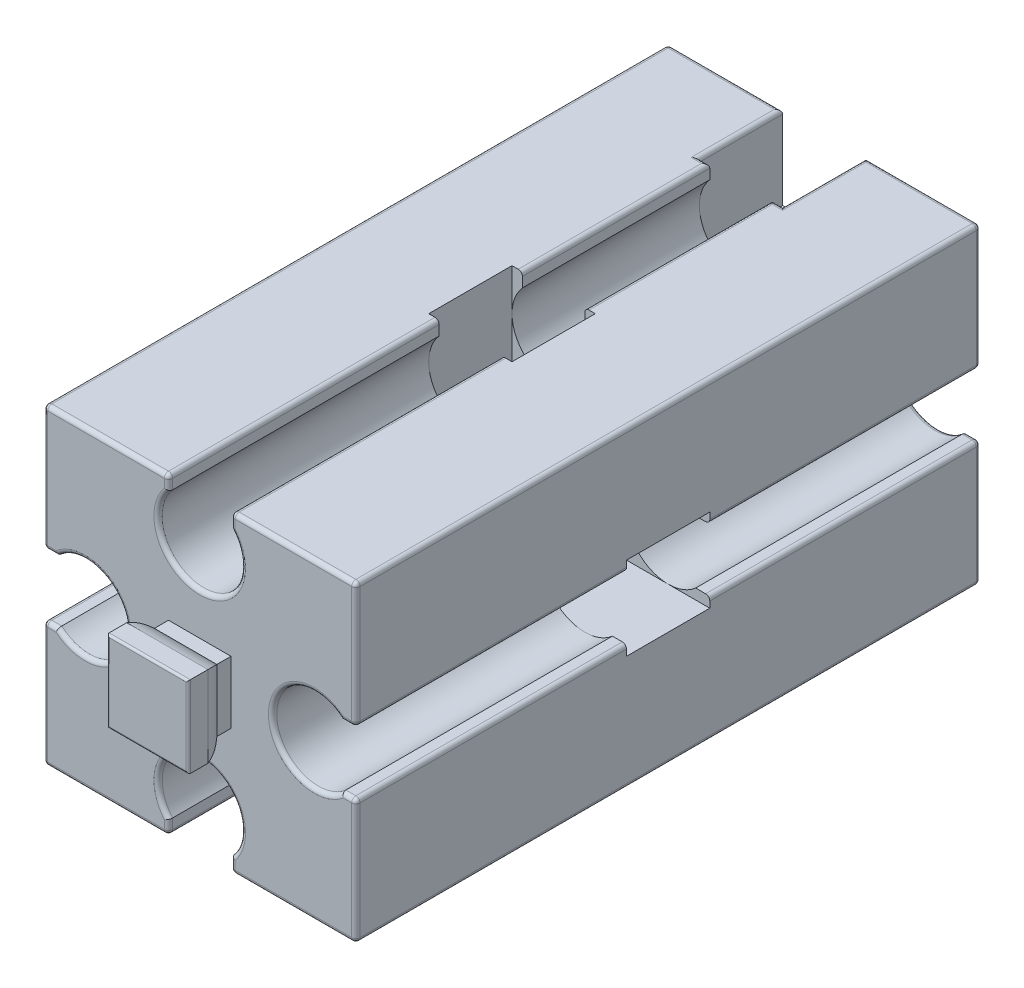
SolidWorks part; units mm, degrees
ref_plane "前视基准面" through (0, 0, 0) normal (0, 0, 1) x (1, 0, 0)
ref_plane "上视基准面" through (0, 0, 0) normal (0, 1, 0) x (1, 0, 0)
ref_plane "右视基准面" through (0, 0, 0) normal (1, 0, 0) x (0, 0, -1)
sketch "草图1" plane through (0, 0, 0) normal (0, 0, 1) x (1, 0, 0)
  line L1 (-7.5, -7.5) -> (7.5, -7.5)
  line L2 (-7.5, -7.5) -> (-7.5, 7.5)
  line L3 (-7.5, 7.5) -> (7.5, 7.5)
  line L4 (7.5, -7.5) -> (7.5, 7.5)
extrude "凸台-拉伸1" add sketch "草图1" against normal blind 30
sketch "草图2" plane through (0, 0, 0) normal (0, 1, 0) x (1, 0, 0)
  line L0 (-7.5, 0) -> (7.5, 0) construction
  line L1 (-1.5, 0) -> (1.5, 0)
  line L2 (-1.5, 0) -> (-1.5, -1)
  line L3 (-1.5, -1) -> (1.5, -1)
  line L4 (1.5, 0) -> (1.5, -1)
extrude "凸台-拉伸2" add sketch "草图2" along normal blind 1.5 and the other way blind 1.5
sketch "草图3" plane through (0, 0, 0) normal (0, 1, 0) x (1, 0, 0)
  line L1 (-1.95, -2.5) -> (1.95, -2.5)
  line L2 (-1.95, -2.5) -> (-1.95, -1.5556)
  line L3 (1.95, -2.5) -> (1.95, -1.5556)
  line L4 (-1.5, 0) -> (-1.5, -1) construction
  line L5 (-1.5, -0.6771) -> (1.5, -0.6771)
  arc A0 (-1.5, -0.6771) -> (-1.95, -1.5556) centre (0, -2) ccw
  arc A1 (1.95, -1.5556) -> (1.5, -0.6771) centre (0, -2) ccw
extrude "凸台-拉伸3" add sketch "草图3" along normal blind 3 and the other way blind 3
sketch "草图5" plane through (0, 0, 0) normal (0, 0, 1) x (1, 0, 0)
  line L0 (-7.5, -7.5) -> (7.5, -7.5) construction
  line L1 (-1.5, -7.5) -> (1.5, -7.5)
  line L2 (-1.5, -7.5) -> (-1.5, -6.8229)
  line L3 (-7.5, 7.5) -> (-7.5, -7.5) construction
  line L4 (1.5, -7.5) -> (1.5, -6.8229)
  line L6 (1.5, 7.5) -> (1.5, 6.8229)
  line L7 (-1.5, 7.5) -> (-1.5, 6.8229)
  line L8 (-1.5, 7.5) -> (1.5, 7.5)
  line L9 (-7.5, 1.5) -> (-6.8229, 1.5)
  line L10 (-7.5, 1.5) -> (-7.5, -1.5)
  line L11 (-7.5, -1.5) -> (-6.8229, -1.5)
  line L12 (7.5, -1.5) -> (6.8229, -1.5)
  line L13 (7.5, 1.5) -> (7.5, -1.5)
  line L14 (7.5, 1.5) -> (6.8229, 1.5)
  arc A0 (1.5, -6.8229) -> (-1.5, -6.8229) centre (0, -5.5) ccw
  arc A1 (1.5, 6.8229) -> (-1.5, 6.8229) centre (0, 5.5) cw
  arc A2 (-6.8229, -1.5) -> (-6.8229, 1.5) centre (-5.5, 0) ccw
  arc A3 (6.8229, -1.5) -> (6.8229, 1.5) centre (5.5, 0) cw
extrude "切除-拉伸2" cut sketch "草图5" against normal through all
sketch "草图6" plane through (0, 7.5, 0) normal (0, 1, 0) x (-1, 0, 0)
  line L0 (1.5, -30) -> (7.5, -30) construction
  line L1 (2, -30) -> (-2, -30)
  line L2 (2, -30) -> (2, -26)
  line L3 (2, -26) -> (-2, -26)
  line L4 (-2, -30) -> (-2, -26)
extrude "切除-拉伸3" cut sketch "草图6" against normal blind 4
sketch "草图9" plane through (0, -7.5, 0) normal (0, -1, 0) x (1, 0, 0)
  line L0 (-7.5, -30) -> (-1.5, -30) construction
  line L1 (-2, -30) -> (2, -30)
  line L2 (-2, -30) -> (-2, -26)
  line L3 (-2, -26) -> (2, -26)
  line L4 (2, -30) -> (2, -26)
extrude "切除-拉伸5" cut sketch "草图9" against normal blind 4
sketch "草图11" plane through (0, 0, 0) normal (0, 1, 0) x (1, 0, 0)
  line L0 (2, 30) -> (-2, 30) construction
  line L1 (-1.5, 30) -> (1.5, 30)
  line L2 (-1.5, 30) -> (-1.5, 29.3229)
  line L4 (1.5, 30) -> (1.5, 29.3229)
  arc A0 (-1.5, 29.3229) -> (1.5, 29.3229) centre (0, 28) ccw
extrude "切除-拉伸6" cut sketch "草图11" against normal through all and the other way through all
sketch "草图12" plane through (0, 0, 0) normal (1, 0, 0) x (0, 0, -1)
  line L0 (-2.5, 3) -> (-2.5, 1.95)
  line L1 (-2.5, 1.95) -> (-1.5556, 1.95)
  line L2 (-2.5, -1.95) -> (-1.5556, -1.95)
  line L5 (-2.5, -1.95) -> (-2.5, -3)
  line L6 (-2.5, 3) -> (-0.6771, 3)
  line L7 (-0.6771, 3) -> (-0.6771, 1.5)
  line L8 (-2.5, -3) -> (-0.6771, -3)
  line L9 (-0.6771, -3) -> (-0.6771, -1.5)
  arc A0 (-0.6771, 1.5) -> (-1.5556, 1.95) centre (-2, 0) ccw
  arc A1 (-1.5556, -1.95) -> (-0.6771, -1.5) centre (-2, 0) ccw
extrude "切除-拉伸7" cut sketch "草图12" against normal up to next and the other way up to next
fillet "圆角2" radius 0.1 4 edges at (-1.95, 0, 2.5) (0, -1.95, 2.5) (1.95, 0, 2.5) (0, 1.95, 2.5)
fillet "圆角3" radius 0.2 54 edges at (-4.75, 7.5, -30) (-7.5, 4.5, -30) (-7.1614, 1.5, -30) (-3.5, 0, -30) (-7.1614, -1.5, -30) (-7.5, -4.5, -30) (-4.75, -7.5, -30) (4.75, -7.5, -30) (7.5, -4.5, -30) (7.1614, -1.5, -30) (3.5, 0, -30) (7.1614, 1.5, -30) (7.5, 4.5, -30) (4.75, 7.5, -30) (7.1614, -1.5, 0) (7.5, -4.5, 0) (4.5, -7.5, 0) (1.5, -7.1614, 0) (0, -3.5, 0) (-1.5, -7.1614, 0) (-4.5, -7.5, 0) (-7.5, -4.5, 0) (-7.1614, -1.5, 0) (-3.5, 0, 0) (-7.1614, 1.5, 0) (-7.5, 4.5, 0) (-4.5, 7.5, 0) (-1.5, 7.1614, 0) (0, 3.5, 0) (1.5, 7.1614, 0) (4.5, 7.5, 0) (7.5, 4.5, 0) (7.1614, 1.5, 0) (3.5, 0, 0) (-7.5, -7.5, -15) (-1.5, -7.5, -13) (-1.75, -7.5, -26) (-2, -7.5, -28) (1.5, -7.5, -13) (7.5, -7.5, -15) (2, -7.5, -28) (1.75, -7.5, -26) (7.5, 7.5, -15) (1.5, 7.5, -13) (1.75, 7.5, -26) (2, 7.5, -28) (-1.75, 7.5, -26) (-1.5, 7.5, -13) (-7.5, 7.5, -15) (-2, 7.5, -28) (-7.5, 1.5, -15) (-7.5, -1.5, -15) (7.5, -1.5, -15) (7.5, 1.5, -15)
sketch "草图13" plane through (7.5, 0, 0) normal (1, 0, 0) x (0, 0, -1)
  circle A0 centre (15, 0) radius 2
extrude "切除-拉伸8" cut sketch "草图13" against normal through all
sketch "草图14" plane through (7.5, 0, 0) normal (1, 0, 0) x (0, 0, -1)
  line L1 (13, -2) -> (17, -2)
  line L2 (13, -2) -> (13, 2)
  line L3 (13, 2) -> (17, 2)
  line L4 (17, -2) -> (17, 2)
extrude "切除-拉伸9" cut sketch "草图14" against normal blind 4
sketch "草图15" plane through (-7.5, 0, 0) normal (-1, 0, 0) x (0, 0, 1)
  line L1 (-17, -2) -> (-13, -2)
  line L2 (-17, -2) -> (-17, 2)
  line L3 (-17, 2) -> (-13, 2)
  line L4 (-13, -2) -> (-13, 2)
extrude "切除-拉伸10" cut sketch "草图15" against normal blind 4
sketch "草图16" plane through (0, 7.5, 0) normal (0, 1, 0) x (-1, 0, 0)
  circle A0 centre (0, -15) radius 2
extrude "切除-拉伸11" cut sketch "草图16" against normal through all
sketch "草图17" plane through (0, 7.5, 0) normal (0, 1, 0) x (-1, 0, 0)
  line L1 (2, -13) -> (-2, -13)
  line L2 (2, -13) -> (2, -17)
  line L3 (2, -17) -> (-2, -17)
  line L4 (-2, -13) -> (-2, -17)
extrude "切除-拉伸12" cut sketch "草图17" against normal blind 4
sketch "草图18" plane through (0, -7.5, 0) normal (0, -1, 0) x (1, 0, 0)
  line L1 (-2, -17) -> (2, -17)
  line L2 (-2, -17) -> (-2, -13)
  line L3 (-2, -13) -> (2, -13)
  line L4 (2, -17) -> (2, -13)
extrude "切除-拉伸13" cut sketch "草图18" against normal blind 4
